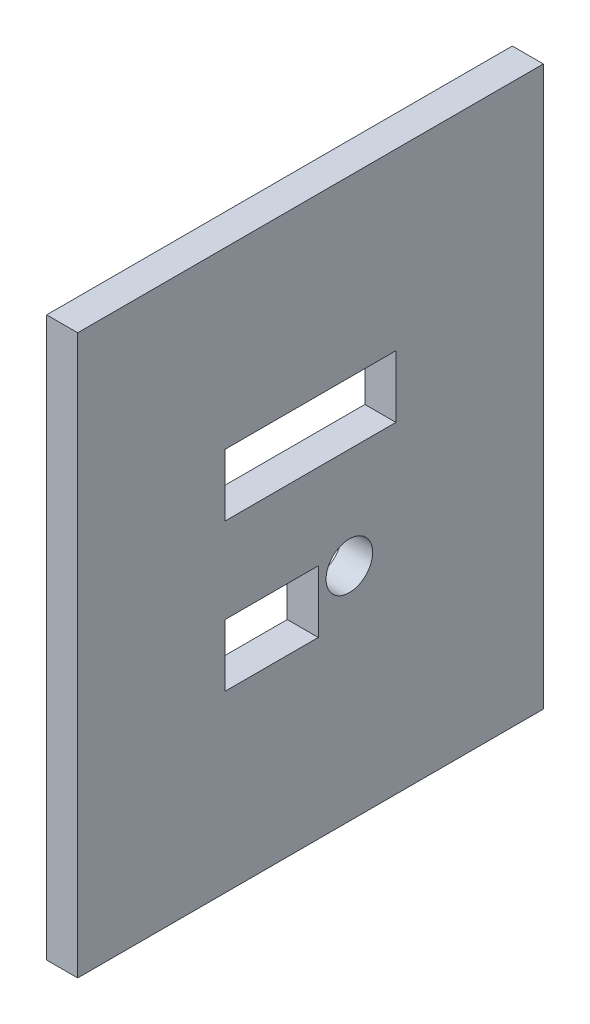
SolidWorks part; units mm, degrees
ref_plane "Front Plane" through (0, 0, 0) normal (0, 0, 1) x (1, 0, 0)
ref_plane "Top Plane" through (0, 0, 0) normal (0, 1, 0) x (1, 0, 0)
ref_plane "Right Plane" through (0, 0, 0) normal (1, 0, 0) x (0, 0, -1)
sketch "Sketch1" plane through (0, 0, 0) normal (1, 0, 0) x (0, 0, -1)
  line L1 (15, -18) -> (-15, -18)
  line L2 (15, -18) -> (15, 18)
  line L3 (15, 18) -> (-15, 18)
  line L4 (-15, -18) -> (-15, 18)
  line L5 (15, -18) -> (-15, 18) construction
  line L6 (15, 18) -> (-15, -18) construction
  point P0 (0, 0)
  dimension "D1" = 30
  dimension "D2" = 36
extrude "Boss-Extrude1" add sketch "Sketch1" along normal blind 2
sketch "Sketch2" plane through (2, 0, 0) normal (1, 0, 0) x (0, 0, -1)
  line L0 (0, 0) -> (-15, 0) construction
  line L1 (5.5, -6.75) -> (-5.5, -6.75)
  line L2 (5.5, -6.75) -> (5.5, 6.75)
  line L3 (5.5, 6.75) -> (-5.5, 6.75)
  line L4 (-5.5, -6.75) -> (-5.5, 6.75)
  line L5 (5.5, -6.75) -> (-5.5, 6.75) construction
  line L6 (5.5, 6.75) -> (-5.5, -6.75) construction
  line L7 (6.5, 6.8524) -> (-5.5, 6.8524)
  line L8 (6.5, 6.8524) -> (6.5, 2.75)
  line L9 (6.5, 2.75) -> (-5.5, 2.75)
  line L10 (-5.5, 6.8524) -> (-5.5, 2.75)
  line L11 (6.5, 6.8524) -> (-5.5, 2.75) construction
  line L12 (6.5, 2.75) -> (-5.5, 6.8524) construction
  line L13 (-15, 18) -> (-15, -18) construction
  line L15 (0.5, -6.75) -> (-5.5, -6.75)
  line L16 (0.5, -6.75) -> (0.5, -2.75)
  line L17 (0.5, -2.75) -> (-5.5, -2.75)
  line L18 (-5.5, -6.75) -> (-5.5, -2.75)
  line L19 (0.5, -6.75) -> (-5.5, -2.75) construction
  line L20 (0.5, -2.75) -> (-5.5, -6.75) construction
  circle A0 centre (2.5, -3.75) radius 1.5
  point P0 (0, 0)
  point P6 (0.5, 4.8012)
  point P15 (-2.5, -4.75)
  dimension "D7" = 3
  dimension "D1" = 13.5
  dimension "D2" = 11
  dimension "D3" = 4
  dimension "D4" = 4
  dimension "D5" = 0
  dimension "D6" = 6
  dimension "D8" = 3
  dimension "D9" = 3
  dimension "D10" = 12
extrude "Cut-Extrude2" cut sketch "Sketch2" against normal blind 10 contours L9 L2 L3 L4 | L16 L17 L4 L1 | A0
